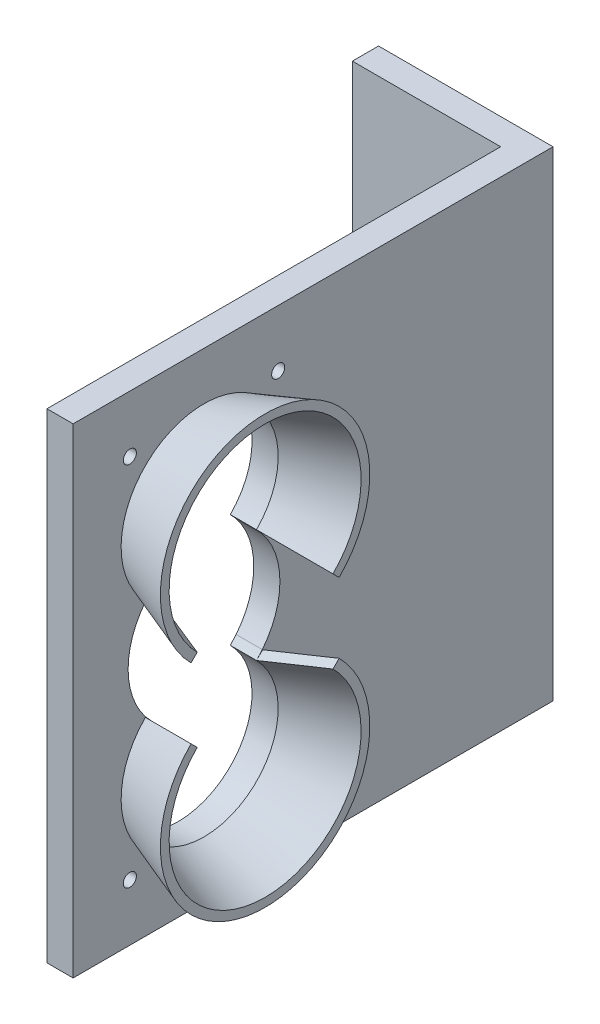
SolidWorks part; units mm, degrees
ref_plane "前视基准面" through (0, 0, 0) normal (0, 0, 1) x (1, 0, 0)
ref_plane "上视基准面" through (0, 0, 0) normal (0, 1, 0) x (1, 0, 0)
ref_plane "右视基准面" through (0, 0, 0) normal (1, 0, 0) x (0, 0, -1)
other "Configuration Table"
sketch "草图1" plane through (0, 0, 0) normal (0, 1, 0) x (1, 0, 0)
  line L0 (5.8824, 27.2843) -> (25.8824, 27.2843)
  line L1 (25.8824, 27.2843) -> (25.8824, -27.7157)
  line L2 (25.8824, -27.7157) -> (22.8824, -27.7157)
  line L3 (22.8824, -27.7157) -> (22.8824, 24.2843)
  line L4 (22.8824, 24.2843) -> (5.8824, 24.2843)
  line L5 (5.8824, 24.2843) -> (5.8824, 27.2843)
  dimension "D1" = 55
  dimension "D2" = 20
  dimension "D3" = 3
  dimension "D4" = 3
extrude "凸台-拉伸1" add sketch "草图1" along normal mid plane 55
ref_plane "基准面1" through (0, 0, -27.2843) normal (0, 0, -1) x (-1, 0, 0)
sketch "草图2" plane through (0, 0, -27.2843) normal (0, 0, -1) x (-1, 0, 0)
  line L0 (-25.8824, 0) -> (-5.8824, 0)
  line L1 (-25.8824, 27.5) -> (-25.8824, -27.5) construction
  line L2 (-5.8824, 27.5) -> (-5.8824, -27.5) construction
  circle A0 centre (-13.3824, -10) radius 1.5
  circle A1 centre (-13.3824, 10) radius 1.5
  dimension "D3" = 3
  dimension "D1" = 7.5
  dimension "D2" = 10
extrude "切除-拉伸1" cut sketch "草图2" against normal blind 3 contours A1 | A0
ref_plane "基准面2" through (25.8824, 0, 0) normal (1, 0, 0) x (0, 0, -1)
sketch "草图3" plane through (25.8824, 0, 0) normal (1, 0, 0) x (0, 0, -1)
  line L0 (-27.7157, 27.5) -> (-27.7157, -27.5) construction
  line L1 (-22.7157, 22.5) -> (-2.7157, 22.5)
  line L2 (-22.7157, 22.5) -> (-22.7157, -22.5)
  line L3 (-22.7157, -22.5) -> (-2.7157, -22.5)
  line L4 (-2.7157, 22.5) -> (-2.7157, -22.5)
  line L5 (-22.7157, 22.5) -> (-2.7157, -22.5) construction
  line L6 (-22.7157, -22.5) -> (-2.7157, 22.5) construction
  line L7 (-12.7157, 22.5) -> (-12.7157, 22)
  line L8 (-12.7157, 12.5) -> (-6.7053, 6.4896)
  line L9 (-12.7157, 12.5) -> (-18.7261, 6.4896)
  line L10 (-12.7157, -12.5) -> (-18.7261, -6.4896)
  line L11 (-12.7157, -12.5) -> (-6.7053, -6.4896)
  line L12 (-12.7157, -22) -> (-12.7157, -22.5)
  line L13 (-12.7157, -4) -> (-12.7157, -21)
  line L14 (-12.7157, 3) -> (-12.7157, -3)
  line L15 (-12.7157, 21) -> (-12.7157, 4)
  line L16 (-22.7157, 0) -> (-2.7157, 0)
  line L17 (-18.7261, 6.4896) -> (-19.3945, 5.744)
  line L18 (-6.7053, 6.4896) -> (-6.0369, 5.744)
  line L19 (-6.0369, -5.744) -> (-6.7053, -6.4896)
  line L20 (-19.3945, -5.744) -> (-18.7261, -6.4896)
  circle A0 centre (-12.7157, 12.5) radius 8.5
  circle A1 centre (-12.7157, -12.5) radius 8.5
  arc A2 (-6.0369, 5.744) -> (-6.0369, -5.744) centre (-13.1949, 0) cw
  arc A3 (-19.3945, 5.744) -> (-19.3945, -5.744) centre (-12.2365, 0) ccw
  circle A4 centre (-12.7157, 12.5) radius 9.5
  circle A5 centre (-12.7157, -12.5) radius 9.5
  circle A6 centre (-4.2157, -21) radius 0.75
  circle A7 centre (-21.2157, -21) radius 0.75
  circle A8 centre (-4.2157, 21) radius 0.75
  circle A9 centre (-21.2157, 21) radius 0.75
  point P0 (0, 0)
  dimension "D6" = 17
  dimension "D7" = 17
  dimension "D8" = 19
  dimension "D9" = 19
  dimension "D11" = 1.5
  dimension "D1" = 45
  dimension "D2" = 20
  dimension "D3" = 5
  dimension "D4" = 10
  dimension "D5" = 10
  dimension "D10" = 1.5
  dimension "D12" = 1.5
extrude "切除-拉伸3" cut sketch "草图3" against normal blind 3 contours L8 A0 L15 | L15 A0 L8 | L9 A0 L15 | L15 A0 L9 | A4 L14 L16 A2 | A5 A2 L16 L14 | A4 A3 L16 L14 | A5 L14 L16 A3 | L13 A1 L11 | L11 A1 L13 | L13 A1 L10 | L10 A1 L13 | A7 | A6 | A9 | A8 | L19 A5 L20 A1 | L17 A4 L18 A0
ref_plane "基准面3" through (32.8824, 0, 0) normal (1, 0, 0) x (0, 0, -1)
sketch "草图4" plane through (32.8824, 0, 0) normal (1, 0, 0) x (0, 0, -1)
  circle A0 centre (-12.7157, 12.5) radius 12
  circle A1 centre (-12.7157, 12.5) radius 11
ref_plane "基准面4" through (0, 0, 12.7157) normal (0, 0, 1) x (0, -1, 0)
sketch "草图5" plane through (0, 0, 12.7157) normal (0, 0, 1) x (0, -1, 0)
  line L0 (-3, 25.8824) -> (-22, 25.8824) construction
  line L1 (-0.5, 32.8824) -> (-24.5, 32.8824) construction
  line L2 (-3, 25.8824) -> (-22, 25.8824)
  line L3 (-0.5, 32.8824) -> (-24.5, 32.8824)
  line L4 (-3, 25.8824) -> (-22, 25.8824)
  line L5 (-22, 25.8824) -> (-24.5, 32.8824)
  line L6 (-22, 25.8824) -> (-21, 25.8824)
  line L7 (-21, 25.8824) -> (-23.5, 32.8824)
  line L8 (-23.5, 32.8824) -> (-24.5, 32.8824)
  line L9 (-12.5, 32.8824) -> (-12.5, 25.8824)
  dimension "D1" = 1
revolve "旋转1" add sketch "草图5" angle 270 mid plane about L9
mirror "镜向1" about plane through (0, 0, 0) normal (0, 1, 0) of "旋转1"
